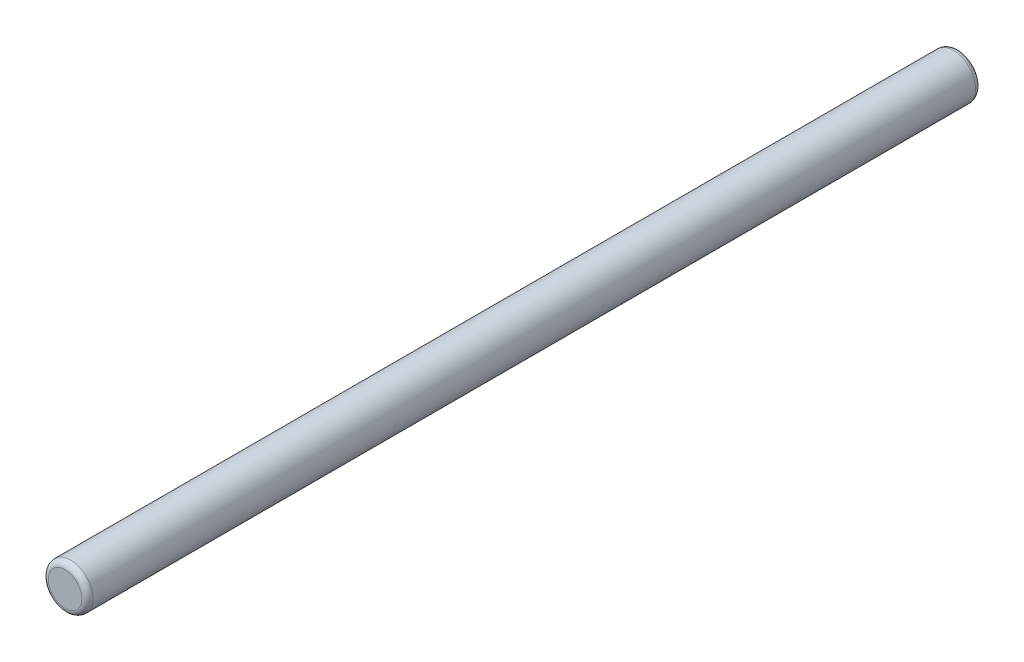
SolidWorks part; units mm, degrees
ref_plane "Plano frontal" through (0, 0, 0) normal (0, 0, 1) x (1, 0, 0)
ref_plane "Plano superior" through (0, 0, 0) normal (0, 1, 0) x (1, 0, 0)
ref_plane "Plano direito" through (0, 0, 0) normal (1, 0, 0) x (0, 0, -1)
sketch "Esboço1" plane through (0, 0, 0) normal (0, 0, 1) x (1, 0, 0)
  circle A0 centre (0, 0) radius 1.2
  dimension "D1" = 2.4
extrude "Ressalto-extrusão1" add sketch "Esboço1" along normal blind 48
fillet "Filete1" radius 0.3 2 edges at (1.2, 0, 0) (1.2, 0, 48)
